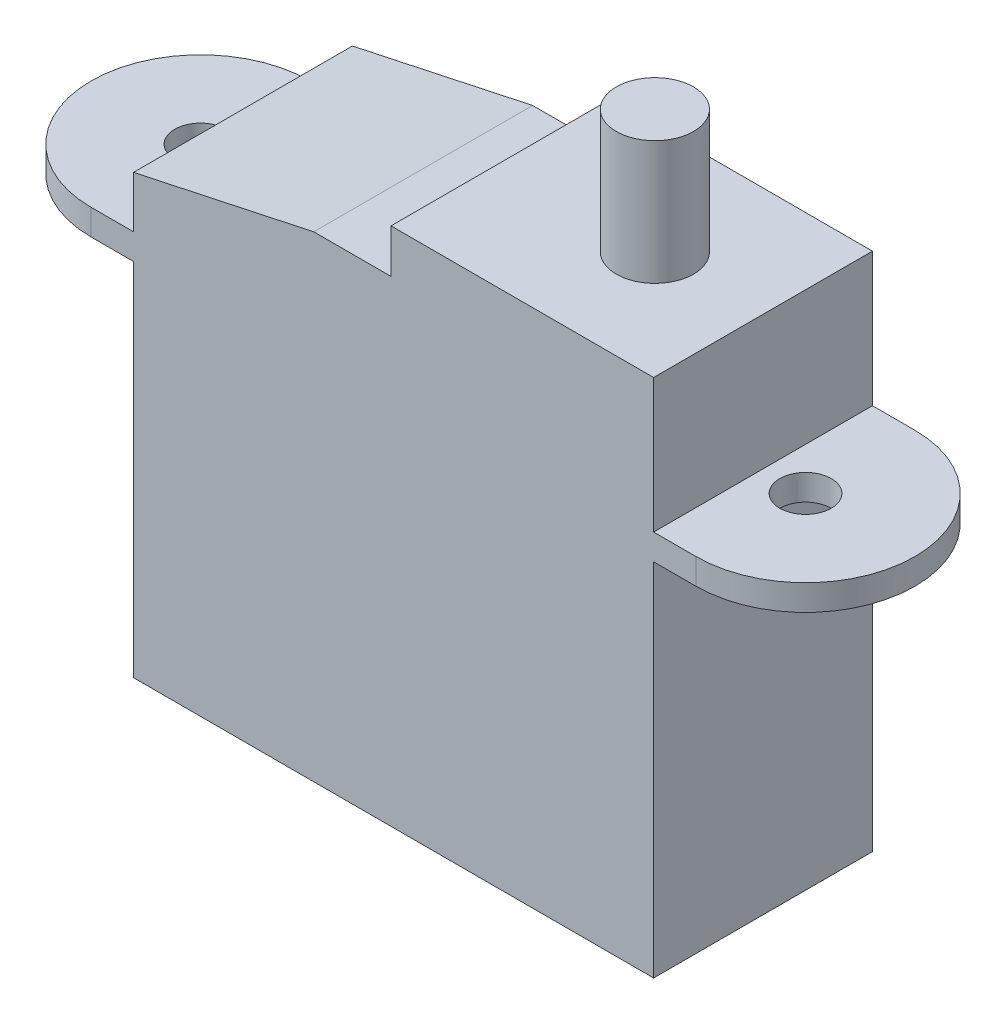
SolidWorks part; units mm, degrees
ref_plane "Front Plane" through (0, 0, 0) normal (0, 0, 1) x (1, 0, 0)
ref_plane "Top Plane" through (0, 0, 0) normal (0, 1, 0) x (1, 0, 0)
ref_plane "Right Plane" through (0, 0, 0) normal (1, 0, 0) x (0, 0, -1)
sketch "Sketch1" plane through (0, 0, 0) normal (0, 1, 0) x (1, 0, 0)
  line L1 (0, 0) -> (20.2, 0)
  line L2 (0, 0) -> (0, 8.5)
  line L3 (0, 8.5) -> (20.2, 8.5)
  line L4 (20.2, 0) -> (20.2, 8.5)
  dimension "D1" = 20.2
  dimension "D2" = 8.5
extrude "Boss-Extrude1" add sketch "Sketch1" along normal blind 14
sketch "Sketch2" plane through (0, 14, 0) normal (0, 1, 0) x (1, 0, 0)
  line L0 (-1.65, 4.25) -> (21.85, 4.25) construction
  line L1 (-1.65, 8.5) -> (21.85, 8.5)
  line L2 (-1.65, 0) -> (21.85, 0)
  line L3 (20.2, 8.5) -> (0, 8.5) construction
  line L4 (0, 0) -> (20.2, 0) construction
  arc A0 (-1.65, 8.5) -> (-1.65, 0) centre (-1.65, 4.25) ccw
  arc A1 (21.85, 0) -> (21.85, 8.5) centre (21.85, 4.25) ccw
  point P2 (10.1, 4.25)
  point P11 (0, 0)
  point P12 (10.1, 0)
  point P13 (-4.6476, 4.25)
  point P14 (10.1, 0)
  dimension "D1" = 23.5
extrude "Boss-Extrude2" add sketch "Sketch2" along normal blind 1
sketch "Sketch3" plane through (0, 15, 0) normal (0, 1, 0) x (1, 0, 0)
  line L0 (21.85, 8.5) -> (-1.65, 8.5) construction
  line L1 (0, 0) -> (20.2, 0)
  line L2 (0, 0) -> (0, 8.5)
  line L3 (0, 8.5) -> (20.2, 8.5)
  line L4 (20.2, 0) -> (20.2, 8.5)
  dimension "D1" = 20.2
extrude "Boss-Extrude3" add sketch "Sketch3" along normal offset from surface (5.2 mm away) 20.2 up to face at (10.1, 0, -4.25)
sketch "Sketch4" plane through (0, 0, 0) normal (0, 0, 1) x (1, 0, 0)
  line L0 (0, 17) -> (7, 18.5)
  line L2 (7, 18.5) -> (10, 18.5)
  line L3 (10, 18.5) -> (10, 20.2)
  line L4 (20.2, 20.2) -> (0, 20.2) construction
  line L5 (10, 20.2) -> (20.2, 20.2)
  line L6 (20.2, 20.2) -> (20.2, 17.6)
  line L7 (20.2, 20.2) -> (20.2, 15) construction
  line L8 (20.2, 17.6) -> (23.4194, 17.6)
  line L9 (23.4194, 17.6) -> (23.4194, 23.7638)
  line L10 (23.4194, 23.7638) -> (-0.8156, 23.7638)
  line L11 (-0.8156, 23.7638) -> (0, 17)
  line L12 (0, 20.2) -> (0, 15) construction
  line L13 (-1.65, 15) -> (0, 15) construction
  point P2 (0, 16.6364)
  dimension "D1" = 2
  dimension "D2" = 1.5
  dimension "D3" = 3
  dimension "D4" = 7
extrude "Cut-Extrude1" cut sketch "Sketch4" against normal blind 20.2
sketch "Sketch5" plane through (0, 15, 0) normal (0, 1, 0) x (1, 0, 0)
  circle A0 centre (-1.65, 4.25) radius 1
  circle A1 centre (21.85, 4.25) radius 1
  dimension "D1" = 2
  dimension "D2" = 2
extrude "Cut-Extrude2" cut sketch "Sketch5" against normal through all
sketch "Sketch6" plane through (0, 20.2, 0) normal (0, 1, 0) x (1, 0, 0)
  line L0 (0, 0) -> (0, 8.5) construction
  line L1 (20.2, 8.5) -> (20.2, 0) construction
  circle A0 centre (16, 4.25) radius 1.5
  point P4 (0, 0)
  point P7 (20.2, 4.25)
  dimension "D2" = 3
  dimension "D1" = 16
extrude "Boss-Extrude4" add sketch "Sketch6" along normal offset from surface (4.8 mm away) 25 up to face at (10.1, 0, -4.25)
